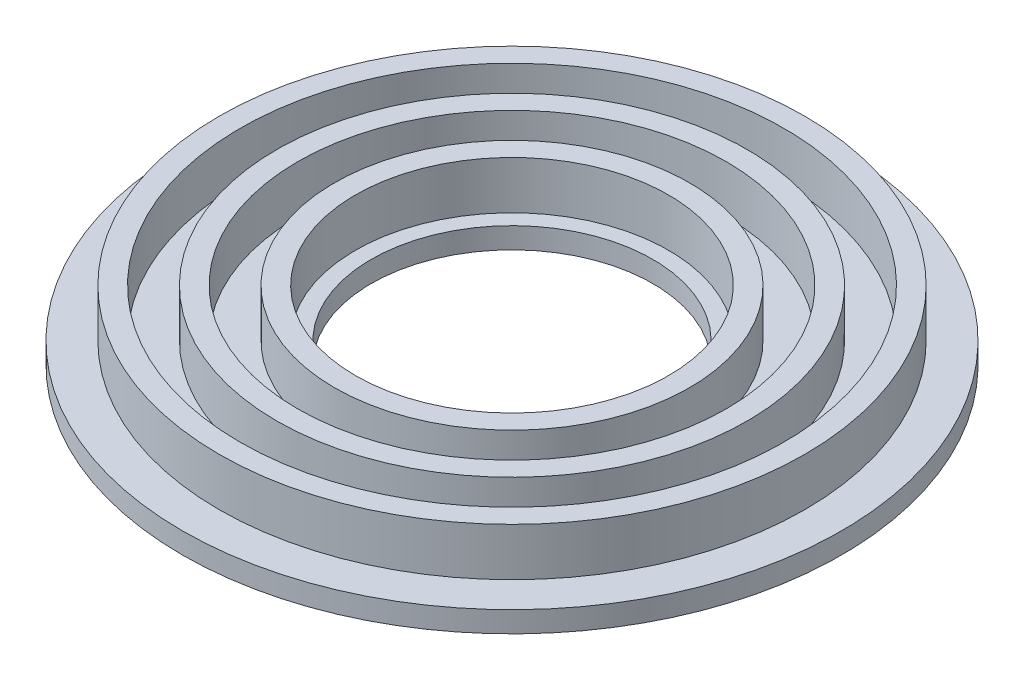
SolidWorks part; units mm, degrees
ref_plane "Alzado" through (0, 0, 0) normal (0, 0, 1) x (1, 0, 0)
ref_plane "Planta" through (0, 0, 0) normal (0, 1, 0) x (1, 0, 0)
ref_plane "Vista lateral" through (0, 0, 0) normal (1, 0, 0) x (0, 0, -1)
sketch "Croquis1" plane through (0, 0, 0) normal (0, 1, 0) x (1, 0, 0)
  circle A0 centre (0, 0) radius 11
  circle A1 centre (0, 0) radius 4 construction
  dimension "D1" = 22
  dimension "D2" = 8
extrude "Extruir1" add sketch "Croquis1" along normal blind 0.7
sketch "Croquis2" plane through (0, 0.7, 0) normal (0, 1, 0) x (1, 0, 0)
  line L0 (0, 4) -> (0, 5.225) construction
  line L1 (0, 5.925) -> (0, 7.15) construction
  line L2 (0, 7.85) -> (0, 9.075) construction
  line L3 (0, 9.775) -> (0, 11) construction
  circle A0 centre (0, 0) radius 9.775
  circle A1 centre (0, 0) radius 9.075
  circle A2 centre (0, 0) radius 5.225
  circle A3 centre (0, 0) radius 5.925
  circle A4 centre (0, 0) radius 7.15
  circle A5 centre (0, 0) radius 7.85
  circle A6 centre (0, 0) radius 4 construction
  circle A7 centre (0, 0) radius 11 construction
  dimension "D1" = 0.7
  dimension "D2" = 0.7
  dimension "D3" = 0.7
extrude "Extruir2" add sketch "Croquis2" along normal blind 1.6 contours A0 A1 | A5 A4 | A3 A2
sketch "Croquis3" plane through (0, 0.7, 0) normal (0, 1, 0) x (1, 0, 0)
  circle A0 centre (0, 0) radius 4.7
  dimension "D1" = 9.4
extrude "Extruir3" cut sketch "Croquis3" against normal blind 1.6
